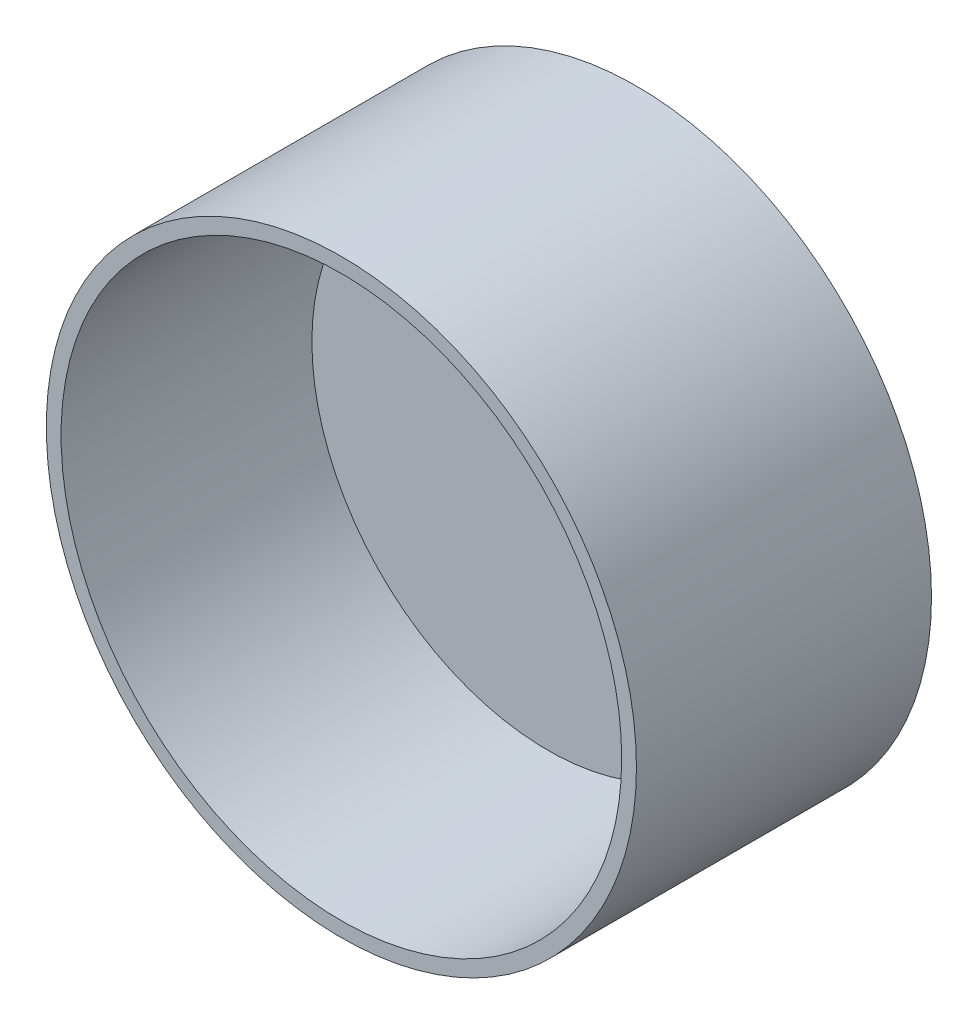
SolidWorks part; units mm, degrees
other "标注1"
sketch "草图5" plane through (100, 100, 200) normal (0.461, 0.308, 0.8323) x (-0.7479, 0.6396, 0.1776)
material "1060 合金"
ref_plane "前视基准面" through (0, 0, 0) normal (0, 0, 1) x (1, 0, 0)
ref_plane "上视基准面" through (0, 0, 0) normal (0, 1, 0) x (1, 0, 0)
ref_plane "右视基准面" through (0, 0, 0) normal (1, 0, 0) x (0, 0, -1)
other "Configuration Table"
sketch "草图11" plane through (0, 0, 0) normal (0, 0, 1) x (1, 0, 0)
  circle A0 centre (0, 0) radius 100
  circle A1 centre (0, 0) radius 95
extrude "凸台-拉伸4" add sketch "草图11" along normal blind 100
sketch "草图12" plane through (0, 0, 0) normal (0, 0, -1) x (-1, 0, 0)
  circle A0 centre (0, 0) radius 80
extrude "凸台-拉伸5" add sketch "草图12" against normal blind 30 separate body
